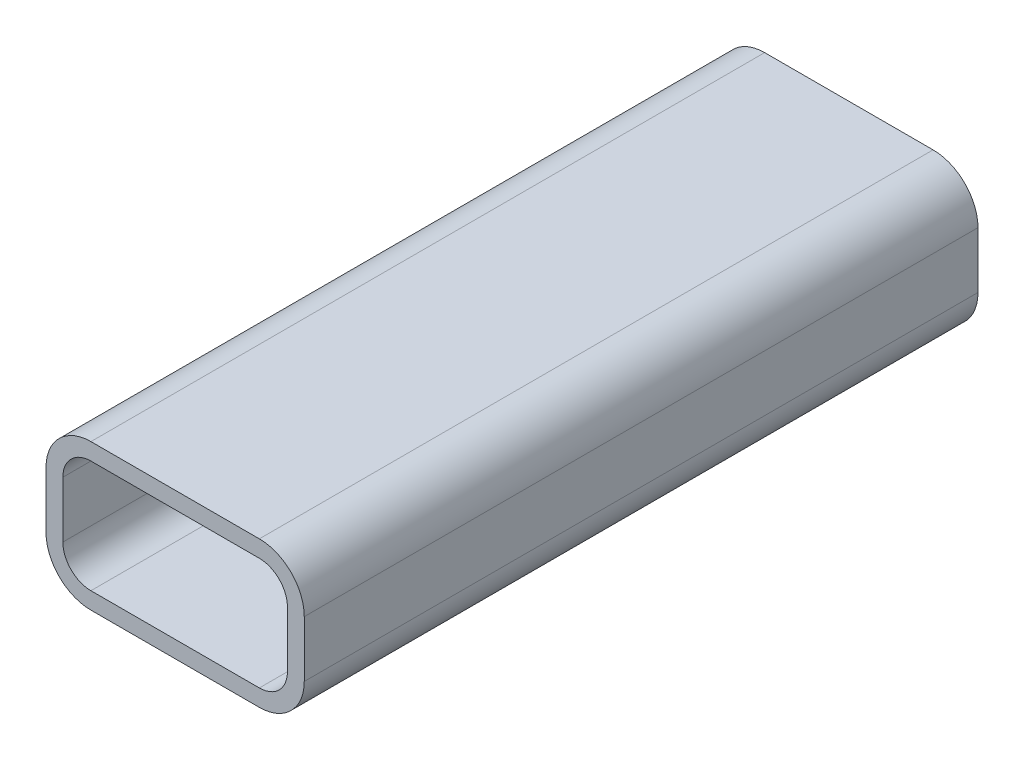
SolidWorks part; units mm, degrees
ref_plane "Front Plane" through (0, 0, 0) normal (0, 0, 1) x (1, 0, 0)
ref_plane "Top Plane" through (0, 0, 0) normal (0, 1, 0) x (1, 0, 0)
ref_plane "Right Plane" through (0, 0, 0) normal (1, 0, 0) x (0, 0, -1)
sketch "Sketch1" plane through (0, 0, 0) normal (0, 0, 1) x (1, 0, 0)
  line L1 (-15, 10) -> (15, 10)
  line L2 (-20, 5) -> (-20, -5)
  line L3 (-15, -10) -> (15, -10)
  line L4 (20, 5) -> (20, -5)
  line L5 (-20, 10) -> (20, -10) construction
  line L6 (-20, -10) -> (20, 10) construction
  arc A0 (15, 10) -> (20, 5) centre (15, 5) cw
  arc A1 (15, -10) -> (20, -5) centre (15, -5) ccw
  arc A2 (-20, -5) -> (-15, -10) centre (-15, -5) ccw
  arc A3 (-15, 10) -> (-20, 5) centre (-15, 5) ccw
  point P0 (0, 0)
  dimension "D3" = 5
  dimension "D1" = 40
  dimension "D2" = 20
extrude "Extrude-Thin1" add sketch "Sketch1" along normal mid plane 120 thin thin type one direction wall 3
